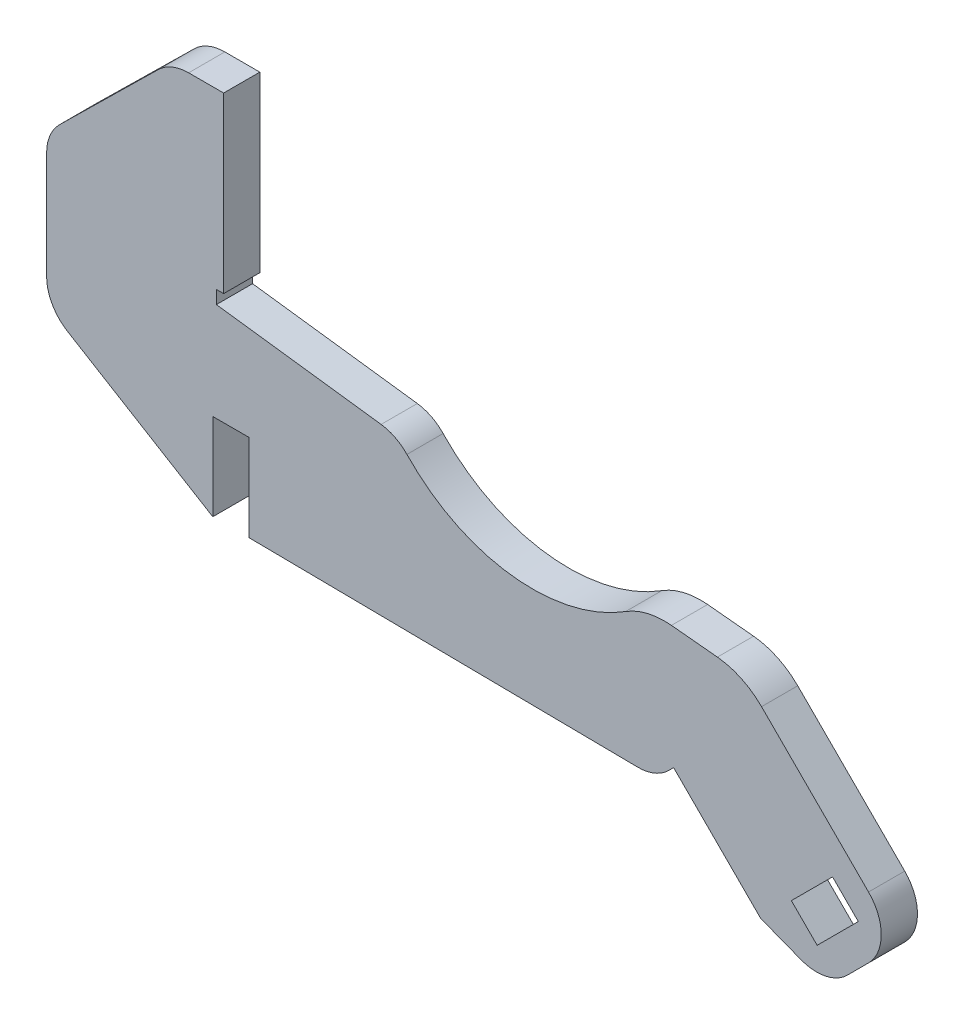
SolidWorks part; units mm, degrees
material "PBT General Purpose"
ref_plane "Front Plane" through (0, 0, 0) normal (0, 0, 1) x (1, 0, 0)
ref_plane "Top Plane" through (0, 0, 0) normal (0, 1, 0) x (1, 0, 0)
ref_plane "Right Plane" through (0, 0, 0) normal (1, 0, 0) x (0, 0, -1)
sketch "frame_outline" plane through (0, 0, 0) normal (0, 0, 1) x (1, 0, 0)
  line L0 (0, 0) -> (0, -0.4) construction
  line L1 (0, 0) -> (0.3, 0) construction
  line L2 (0, -0.4) -> (-0.05, -0.4) construction
  line L3 (0, 0) -> (4.9667, -4.9667) construction
  line L63 (-0.05, -0.4) -> (-0.05, -1.6)
  line L64 (-0.05, -0.4) -> (-0.4144, -0.4)
  line L65 (-0.4144, -0.4) -> (-1.2727, -1.2438)
  line L66 (-1.2727, -1.2438) -> (-1.2727, -2.2778)
  line L67 (-1.2727, -2.2778) -> (-0.125, -2.9724)
  line L68 (-0.125, -2.9724) -> (-0.125, -2.3724)
  line L69 (-0.125, -2.3724) -> (0.125, -2.3724)
  line L70 (0.125, -2.3724) -> (0.125, -2.9724)
  line L71 (0.125, -2.9724) -> (2.9356, -3.0041)
  line L72 (2.9356, -3.0041) -> (3.0582, -2.8815)
  line L73 (3.0582, -2.8815) -> (3.6593, -3.4825)
  line L74 (3.6593, -3.4825) -> (4.1203, -3.6607)
  line L75 (4.1203, -3.6607) -> (4.6167, -3.1643)
  line L76 (4.6167, -3.1643) -> (3.5388, -2.0864)
  line L77 (3.5388, -2.0864) -> (2.8549, -2.0196)
  line L78 (-0.1, -1.6906) -> (-0.1, -1.6)
  line L79 (-0.1, -1.6) -> (-0.05, -1.6)
  line L80 (3.8714, -3.2704) -> (4.0496, -3.4486)
  line L81 (3.8714, -3.2704) -> (4.1557, -2.9861)
  line L82 (4.0496, -3.4486) -> (4.3339, -3.1643)
  line L83 (4.1557, -2.9861) -> (4.3339, -3.1643)
  line L84 (0, -0.4) -> (0, -4.6335) construction
  line L85 (3.6593, -3.4825) -> (3.8714, -3.2704) construction
  line L86 (1.1495, -1.8531) -> (-0.1, -1.6906)
  arc A0 (1.1495, -1.8531) -> (2.8549, -2.0196) centre (2.0839, -1.1001) ccw
  point P25 (0, -2.3724)
  dimension "D2" = 0.3
  dimension "D3" = 0.4
  dimension "D8" = 1.2
  dimension "D4" = 45
  dimension "D1" = 0.05
  dimension "D5" = 0.125
  dimension "D6" = 0.25
  dimension "D7" = 0.05
  dimension "D9" = 0.6
  dimension "D10" = 0.85
  dimension "D11" = 0.252
  dimension "D12" = 0.402
  dimension "D13" = 0.3
  dimension "D14" = 0.2
  dimension "D15" = 0.2
  dimension "D16" = 0.1
  dimension "D17" = 4.2
extrude "Boss-Extrude1" add sketch "frame_outline" along normal mid plane 0.25
fillet "Fillet1" radius 0.3 7 edges at (4.6167, -3.1643, 0) (4.1203, -3.6607, 0) (1.1495, -1.8531, 0) (-0.4144, -0.4, 0) (-1.2727, -1.2438, 0) (-1.2727, -2.2778, 0) (2.9356, -3.0041, 0)
fillet "Fillet2" radius 0.5 2 edges at (3.5388, -2.0864, 0) (2.8549, -2.0196, 0)
equation "\"t\"= 0.25'thickness of the sheets"
equation "\"t_cf\" = 0.115'thickness of single carbon fiber layer"
equation "\"t_kapton\" = 0.025'thickness of single Kapton flex layer"
equation "\"t_fr4\" = 0.1'thickness of FR4 with copper layer"
equation "\"joint_flex\"= 0.1'Width of flextures gap"
equation "\"joint_flex_eff\"= 0.02'Width of flecture after castelation"
equation "\"joint_fold\"= 0.2'Width of folding joints for 90deg fold"
equation "\"gap_tolerance\"= 0.002'Width to have interfecence fit between carbon fiber inserts"
equation "\"assemble_angle\"= 90'Angle of assembly parts"
equation "\"D1@Boss-Extrude1\"=\"t\""
equation "\"link_lift\"= 0.5'Actuation linkage amplification for the lift motion"
equation "\"link_swing\"= 0.45'Actuation linkage amplification for the swing motion"
equation "\"D1@frame_outline\"=\"joint_flex\"/2"
equation "\"D5@frame_outline\"=\"t\"/2"
equation "\"D6@frame_outline\"=\"t\""
equation "\"D11@frame_outline\"=\"t\"+\"gap_tolerance\""
equation "\"D12@frame_outline\"=0.4+\"gap_tolerance\""
equation "\"D10@frame_outline\"=0.80mm+0.05"
